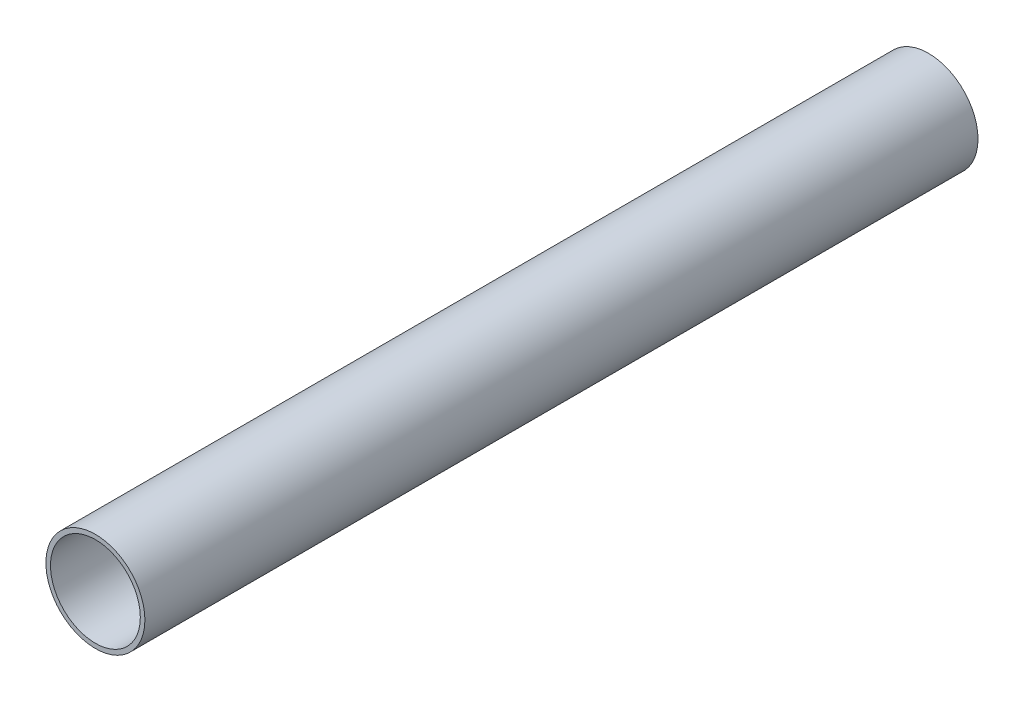
SolidWorks part; units mm, degrees
material "Acier galvanisé"
ref_plane "Plan de face" through (0, 0, 0) normal (0, 0, 1) x (1, 0, 0)
ref_plane "Plan de dessus" through (0, 0, 0) normal (0, 1, 0) x (1, 0, 0)
ref_plane "Plan de droite" through (0, 0, 0) normal (1, 0, 0) x (0, 0, -1)
sketch "Esquisse1" plane through (0, 0, 0) normal (0, 0, 1) x (1, 0, 0)
  circle A0 centre (0, 0) radius 17.4625
  circle A1 centre (0, 0) radius 19.2405
  dimension "D1" = 34.925
  dimension "D2" = 38.481
extrude "Boss.-Extru.1" add sketch "Esquisse1" along normal blind 914.4
sketch "Esquisse3" plane through (0, 0, 914.4) normal (0, 0, 1) x (1, 0, 0)
  circle A0 centre (0, 0) radius 19.2405
  dimension "D1" = 38.481
extrude "Enlèv. mat.-Extru.1" cut sketch "Esquisse3" against normal blind 63.5
sketch "Esquisse4" plane through (0, 0, 850.9) normal (0, 0, 1) x (1, 0, 0)
  circle A0 centre (0, 0) radius 19.2405
  dimension "D1" = 38.481
extrude "Enlèv. mat.-Extru.2" cut sketch "Esquisse4" against normal blind 527.05
